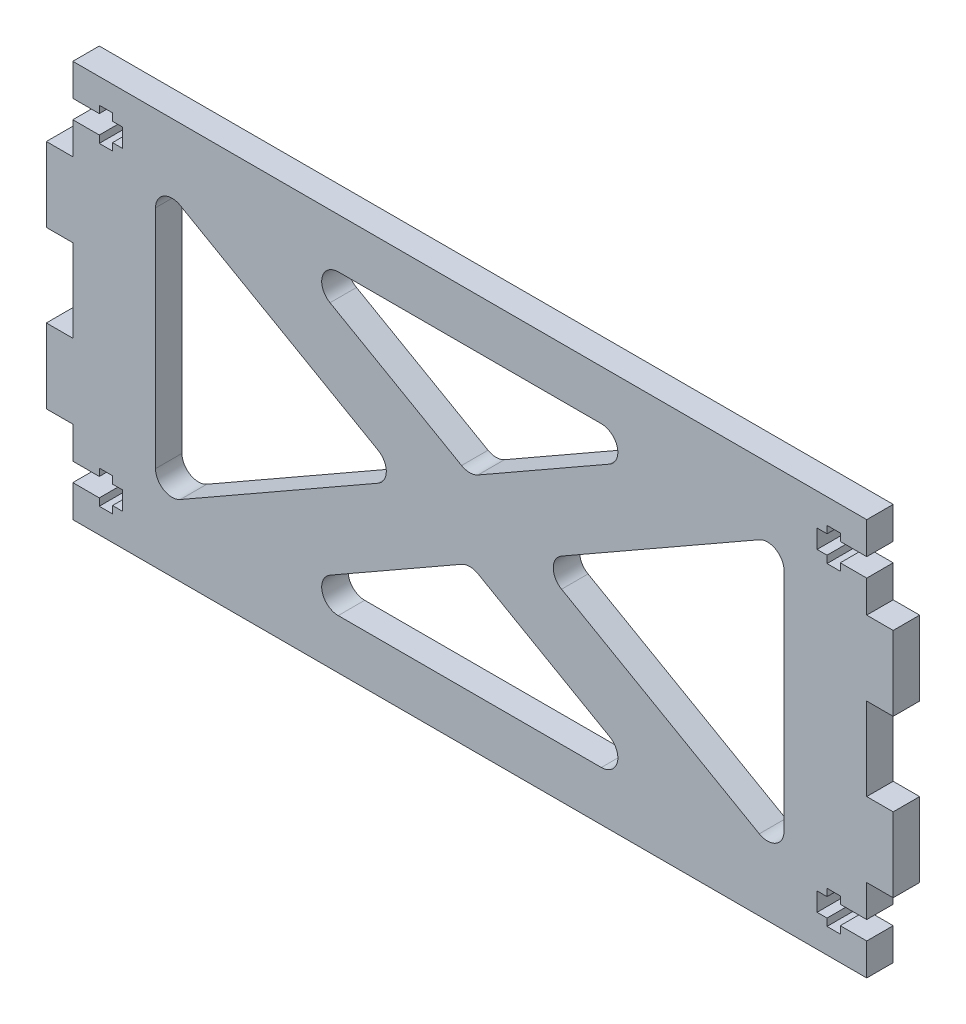
SolidWorks part; units mm, degrees
ref_plane "Спереди" through (0, 0, 0) normal (0, 0, 1) x (1, 0, 0)
ref_plane "Сверху" through (0, 0, 0) normal (0, 1, 0) x (1, 0, 0)
ref_plane "Справа" through (0, 0, 0) normal (1, 0, 0) x (0, 0, -1)
sketch "Эскиз1" plane through (0, 0, 0) normal (0, 0, 1) x (1, 0, 0)
  line L0 (55, 0) -> (-55, 0) construction
  line L1 (-60, -30) -> (60, -30)
  line L2 (-60, -30) -> (-60, 30)
  line L3 (-60, 30) -> (60, 30)
  line L4 (60, -30) -> (60, 30)
  line L5 (-60, -30) -> (60, 30) construction
  line L6 (-60, 30) -> (60, -30) construction
  line L7 (60, 17.5) -> (64, 17.5)
  line L8 (60, 17.5) -> (60, 6.25)
  line L9 (60, 6.25) -> (64, 6.25)
  line L10 (64, 17.5) -> (64, 6.25)
  line L15 (64, -17.5) -> (64, -6.25)
  line L16 (60, -6.25) -> (64, -6.25)
  line L17 (60, -17.5) -> (60, -6.25)
  line L18 (60, -17.5) -> (64, -17.5)
  line L19 (0, -55) -> (0, 55) construction
  line L20 (-60, -17.5) -> (-64, -17.5)
  line L21 (-60, -17.5) -> (-60, -6.25)
  line L22 (-60, -6.25) -> (-64, -6.25)
  line L23 (-64, -17.5) -> (-64, -6.25)
  line L24 (-64, 17.5) -> (-64, 6.25)
  line L25 (-60, 6.25) -> (-64, 6.25)
  line L26 (-60, 17.5) -> (-60, 6.25)
  line L27 (-60, 17.5) -> (-64, 17.5)
  line L40 (60, -24.4098) -> (62.2361, -25.5279)
  point P0 (0, 0)
  dimension "D1" = 120
  dimension "D2" = 60
  dimension "D3" = 12.5
  dimension "D4" = 12.5
  dimension "D5" = 4
extrude "Бобышка-Вытянуть1" add sketch "Эскиз1" along normal blind 4 contours L1 L4 L3 L2 | L23 L20 L2 L22 | L2 L27 L24 L25 | L10 L7 L4 L9 | L4 L18 L15 L16
sketch "Эскиз2" plane through (0, 0, 4) normal (0, 0, 1) x (1, 0, 0)
  line L0 (-60, 17.5) -> (-60, 30) construction
  line L1 (-60, 25.15) -> (-52.5, 25.15)
  line L2 (-60, 25.15) -> (-60, 22.35)
  line L3 (-60, 22.35) -> (-52.5, 22.35)
  line L4 (-52.5, 25.15) -> (-52.5, 22.35)
  line L5 (0, -2.2) -> (0, 2.2) construction
  line L6 (-56, 21.25) -> (-54, 21.25)
  line L7 (-56, 21.25) -> (-56, 26.25)
  line L8 (-56, 26.25) -> (-54, 26.25)
  line L9 (-54, 21.25) -> (-54, 26.25)
  line L10 (-56, 21.25) -> (-54, 26.25) construction
  line L11 (-56, 26.25) -> (-54, 21.25) construction
  line L12 (56, 26.25) -> (54, 21.25) construction
  line L13 (56, 21.25) -> (54, 26.25) construction
  line L14 (54, 21.25) -> (54, 26.25)
  line L15 (56, 26.25) -> (54, 26.25)
  line L16 (56, 21.25) -> (56, 26.25)
  line L17 (56, 21.25) -> (54, 21.25)
  line L18 (52.5, 25.15) -> (52.5, 22.35)
  line L19 (60, 22.35) -> (52.5, 22.35)
  line L20 (60, 25.15) -> (60, 22.35)
  line L21 (60, 25.15) -> (52.5, 25.15)
  line L22 (2.2, 0) -> (-2.2, 0) construction
  line L23 (56, -21.25) -> (54, -26.25) construction
  line L24 (56, -26.25) -> (54, -21.25) construction
  line L25 (-56, -26.25) -> (-54, -21.25) construction
  line L26 (-56, -21.25) -> (-54, -26.25) construction
  line L27 (60, -25.15) -> (52.5, -25.15)
  line L28 (60, -25.15) -> (60, -22.35)
  line L29 (60, -22.35) -> (52.5, -22.35)
  line L30 (52.5, -25.15) -> (52.5, -22.35)
  line L31 (56, -21.25) -> (54, -21.25)
  line L32 (56, -21.25) -> (56, -26.25)
  line L33 (56, -26.25) -> (54, -26.25)
  line L34 (54, -21.25) -> (54, -26.25)
  line L35 (-54, -21.25) -> (-54, -26.25)
  line L36 (-56, -26.25) -> (-54, -26.25)
  line L37 (-56, -21.25) -> (-56, -26.25)
  line L38 (-56, -21.25) -> (-54, -21.25)
  line L39 (-52.5, -25.15) -> (-52.5, -22.35)
  line L40 (-60, -22.35) -> (-52.5, -22.35)
  line L41 (-60, -25.15) -> (-60, -22.35)
  line L42 (-60, -25.15) -> (-52.5, -25.15)
  point P6 (-60, 23.75)
  point P7 (-60, 23.75)
  point P8 (-55, 23.75)
  point P14 (-52.5, 23.75)
  point P25 (55, 23.75)
  point P44 (55, -23.75)
  point P45 (-55, -23.75)
  dimension "D1" = 2.8
  dimension "D2" = 7.5
  dimension "D3" = 5
  dimension "D4" = 2
  dimension "D5" = 4
extrude "Вырез-Вытянуть1" cut sketch "Эскиз2" against normal blind 4 contours L39 L40 L41 L42 | L38 L35 L36 L37 | L4 L3 L2 L1 | L8 L9 L6 L7 | L15 L14 L17 L16 | L18 L19 L20 L21 | L31 L34 L33 L32 | L30 L29 L28 L27
sketch "Эскиз3" plane through (0, 0, 4) normal (0, 0, 1) x (1, 0, 0)
  line L0 (-60, 30) -> (60, 30) construction
  line L1 (-52.5, -30) -> (52.5, -30) construction
  line L2 (-52.5, -30) -> (-52.5, 30) construction
  line L3 (-52.5, 30) -> (52.5, 30) construction
  line L4 (52.5, -30) -> (52.5, 30) construction
  line L5 (-52.5, -30) -> (52.5, 30) construction
  line L6 (-52.5, 30) -> (52.5, -30) construction
  line L7 (-52.5, 25.15) -> (-52.5, 22.35) construction
  line L8 (-29.2972, 22.5) -> (29.2972, 22.5)
  line L9 (-29.2972, 22.5) -> (0, 5.7588)
  line L10 (-47.5, -21.3841) -> (-10.0778, 0)
  line L11 (-47.5, -21.3841) -> (-47.5, 21.3841)
  line L12 (-47.5, 21.3841) -> (-10.0778, 0)
  line L13 (-52.5, 22.5) -> (52.5, 22.5) construction
  line L14 (-50.0193, 34.3412) -> (54.9807, -25.6588) construction
  line L15 (-54.9807, -25.6588) -> (50.0193, 34.3412) construction
  line L16 (-47.5, -30) -> (-47.5, 30) construction
  line L17 (-54.9807, 25.6588) -> (50.0193, -34.3412) construction
  line L18 (52.5, -24.2412) -> (54.9807, -25.6588)
  line L19 (0, 5.7588) -> (29.2972, 22.5)
  line L20 (42.4222, -30) -> (50.0193, -34.3412)
  line L21 (0, -2.2) -> (0, 2.2) construction
  line L22 (47.5, 21.3841) -> (10.0778, 0)
  line L23 (47.5, -21.3841) -> (47.5, 21.3841)
  line L24 (47.5, -21.3841) -> (10.0778, 0)
  line L25 (2.2, 0) -> (-2.2, 0) construction
  line L26 (0, -5.7588) -> (29.2972, -22.5)
  line L27 (-29.2972, -22.5) -> (0, -5.7588)
  line L28 (-29.2972, -22.5) -> (29.2972, -22.5)
  point P0 (0, 0)
  dimension "D1" = 7.5
  dimension "D2" = 5
  dimension "D3" = 5
  dimension "D4" = 5
  dimension "D5" = 5
extrude "Вырез-Вытянуть2" cut sketch "Эскиз3" against normal through all contours L12 L11 L10 | L9 L19 L8 | L24 L23 L22 | L27 L28 L26
fillet "Скругление1" radius 2.5 12 edges at (-29.2972, 22.5, 2) (0, 5.7588, 2) (29.2972, 22.5, 2) (47.5, 21.3841, 2) (10.0778, 0, 2) (47.5, -21.3841, 2) (29.2972, -22.5, 2) (-47.5, -21.3841, 2) (-29.2972, -22.5, 2) (0, -5.7588, 2) (-47.5, 21.3841, 2) (-10.0778, 0, 2)
